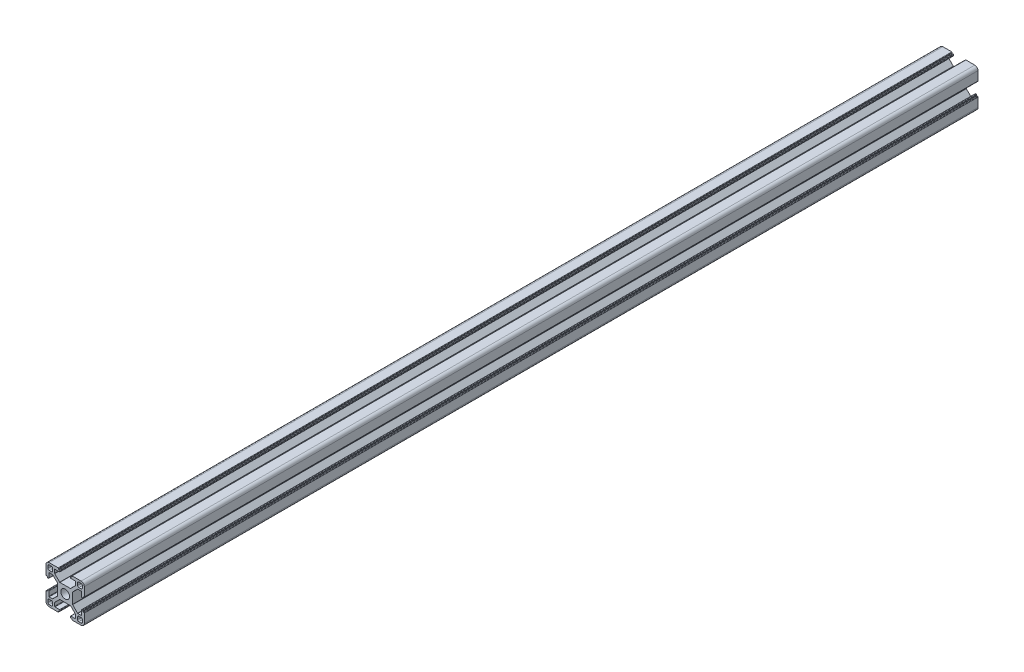
SolidWorks part; units mm, degrees
ref_plane "Front Plane" through (0, 0, 0) normal (0, 0, 1) x (1, 0, 0)
ref_plane "Top Plane" through (0, 0, 0) normal (0, 1, 0) x (1, 0, 0)
ref_plane "Right Plane" through (0, 0, 0) normal (1, 0, 0) x (0, 0, -1)
sketch "Model" plane through (0, 0, 0) normal (0, 0, 1) x (1, 0, 0)
  line L0 (21.5, 27) -> (25, 27)
  line L1 (27, 25) -> (27, 21.5)
  line L2 (25, 19.5) -> (21.5, 19.5)
  line L3 (19.5, 21.5) -> (19.5, 25)
  line L4 (21.5, -27) -> (25, -27)
  line L5 (27, -25) -> (27, -21.5)
  line L6 (25, -19.5) -> (21.5, -19.5)
  line L7 (19.5, -21.5) -> (19.5, -25)
  line L8 (0, 11.6) -> (-8.2402, 11.6)
  line L9 (-8.6645, 11.7757) -> (-16.3243, 19.4355)
  line L10 (-16.5, 19.8598) -> (-16.5, 25)
  line L11 (-15.9, 25.6) -> (-8.8, 25.6)
  line L12 (-8.2, 26.2) -> (-8.2, 27.4)
  line L13 (-8.8, 28) -> (-9.8, 28)
  line L14 (-10.4, 28.6) -> (-10.4, 29.4)
  line L15 (-11, 30) -> (-25, 30)
  line L16 (-30, 25) -> (-30, 11)
  line L17 (-29.4, 10.4) -> (-28.6, 10.4)
  line L18 (-28, 9.8) -> (-28, 8.8)
  line L19 (-27.4, 8.2) -> (-26.2, 8.2)
  line L20 (-25.6, 8.8) -> (-25.6, 15.9)
  line L21 (-25, 16.5) -> (-19.8598, 16.5)
  line L22 (-19.4355, 16.3243) -> (-11.7757, 8.6645)
  line L23 (-11.6, 8.2402) -> (-11.6, 0)
  line L24 (-11.6, 0) -> (-11.6, -8.2402)
  line L25 (-11.7757, -8.6645) -> (-19.4355, -16.3243)
  line L26 (-19.8598, -16.5) -> (-25, -16.5)
  line L27 (-25.6, -15.9) -> (-25.6, -8.8)
  line L28 (-26.2, -8.2) -> (-27.4, -8.2)
  line L29 (-28, -8.8) -> (-28, -9.8)
  line L30 (-28.6, -10.4) -> (-29.4, -10.4)
  line L31 (-30, -11) -> (-30, -25)
  line L32 (-25, -30) -> (-11, -30)
  line L33 (-10.4, -29.4) -> (-10.4, -28.6)
  line L34 (-9.8, -28) -> (-8.8, -28)
  line L35 (-8.2, -27.4) -> (-8.2, -26.2)
  line L36 (-8.8, -25.6) -> (-15.9, -25.6)
  line L37 (-16.5, -25) -> (-16.5, -19.8598)
  line L38 (-16.3243, -19.4355) -> (-8.6645, -11.7757)
  line L39 (-8.2402, -11.6) -> (0, -11.6)
  line L40 (0, -11.6) -> (8.2402, -11.6)
  line L41 (8.6645, -11.7757) -> (16.3243, -19.4355)
  line L42 (16.5, -19.8598) -> (16.5, -25)
  line L43 (15.9, -25.6) -> (8.8, -25.6)
  line L44 (8.2, -26.2) -> (8.2, -27.4)
  line L45 (8.8, -28) -> (9.8, -28)
  line L46 (10.4, -28.6) -> (10.4, -29.4)
  line L47 (11, -30) -> (25, -30)
  line L48 (30, -25) -> (30, -11)
  line L49 (29.4, -10.4) -> (28.6, -10.4)
  line L50 (28, -9.8) -> (28, -8.8)
  line L51 (27.4, -8.2) -> (26.2, -8.2)
  line L52 (25.6, -8.8) -> (25.6, -15.9)
  line L53 (25, -16.5) -> (19.8598, -16.5)
  line L54 (19.4355, -16.3243) -> (11.7757, -8.6645)
  line L55 (11.6, -8.2402) -> (11.6, 0)
  line L56 (11.6, 0) -> (11.6, 8.2402)
  line L57 (11.7757, 8.6645) -> (19.6113, 16.5)
  line L58 (19.6113, 16.5) -> (25, 16.5)
  line L59 (25.6, 15.9) -> (25.6, 8.8)
  line L60 (26.2, 8.2) -> (27.4, 8.2)
  line L61 (28, 8.8) -> (28, 9.8)
  line L62 (28.6, 10.4) -> (29.4, 10.4)
  line L63 (30, 11) -> (30, 25)
  line L64 (25, 30) -> (11, 30)
  line L65 (10.4, 29.4) -> (10.4, 28.6)
  line L66 (9.8, 28) -> (8.8, 28)
  line L67 (8.2, 27.4) -> (8.2, 26.2)
  line L68 (8.8, 25.6) -> (15.9, 25.6)
  line L69 (16.5, 25) -> (16.5, 19.8598)
  line L70 (16.3243, 19.4355) -> (8.6645, 11.7757)
  line L71 (8.2402, 11.6) -> (0, 11.6)
  line L72 (-21.5, -27) -> (-25, -27)
  line L73 (-27, -25) -> (-27, -21.5)
  line L74 (-25, -19.5) -> (-21.5, -19.5)
  line L75 (-19.5, -21.5) -> (-19.5, -25)
  line L76 (-21.5, 27) -> (-25, 27)
  line L77 (-27, 25) -> (-27, 21.5)
  line L78 (-25, 19.5) -> (-21.5, 19.5)
  line L79 (-19.5, 21.5) -> (-19.5, 25)
  circle A0 centre (0, 0) radius 6.8
  arc A1 (21.5, 27) -> (19.5, 25) centre (21.5, 25) ccw
  arc A2 (27, 25) -> (25, 27) centre (25, 25) ccw
  arc A3 (25, 19.5) -> (27, 21.5) centre (25, 21.5) ccw
  arc A4 (19.5, 21.5) -> (21.5, 19.5) centre (21.5, 21.5) ccw
  arc A5 (19.5, -25) -> (21.5, -27) centre (21.5, -25) ccw
  arc A6 (25, -27) -> (27, -25) centre (25, -25) ccw
  arc A7 (27, -21.5) -> (25, -19.5) centre (25, -21.5) ccw
  arc A8 (21.5, -19.5) -> (19.5, -21.5) centre (21.5, -21.5) ccw
  arc A9 (-8.6645, 11.7757) -> (-8.2402, 11.6) centre (-8.2402, 12.2) ccw
  arc A10 (-16.5, 19.8598) -> (-16.3243, 19.4355) centre (-15.9, 19.8598) ccw
  arc A11 (-15.9, 25.6) -> (-16.5, 25) centre (-15.9, 25) ccw
  arc A12 (-8.8, 25.6) -> (-8.2, 26.2) centre (-8.8, 26.2) ccw
  arc A13 (-8.2, 27.4) -> (-8.8, 28) centre (-8.8, 27.4) ccw
  arc A14 (-10.4, 28.6) -> (-9.8, 28) centre (-9.8, 28.6) ccw
  arc A15 (-10.4, 29.4) -> (-11, 30) centre (-11, 29.4) ccw
  arc A16 (-25, 30) -> (-30, 25) centre (-25, 25) ccw
  arc A17 (-30, 11) -> (-29.4, 10.4) centre (-29.4, 11) ccw
  arc A18 (-28, 9.8) -> (-28.6, 10.4) centre (-28.6, 9.8) ccw
  arc A19 (-28, 8.8) -> (-27.4, 8.2) centre (-27.4, 8.8) ccw
  arc A20 (-26.2, 8.2) -> (-25.6, 8.8) centre (-26.2, 8.8) ccw
  arc A21 (-25, 16.5) -> (-25.6, 15.9) centre (-25, 15.9) ccw
  arc A22 (-19.4355, 16.3243) -> (-19.8598, 16.5) centre (-19.8598, 15.9) ccw
  arc A23 (-11.6, 8.2402) -> (-11.7757, 8.6645) centre (-12.2, 8.2402) ccw
  arc A24 (-11.7757, -8.6645) -> (-11.6, -8.2402) centre (-12.2, -8.2402) ccw
  arc A25 (-19.8598, -16.5) -> (-19.4355, -16.3243) centre (-19.8598, -15.9) ccw
  arc A26 (-25.6, -15.9) -> (-25, -16.5) centre (-25, -15.9) ccw
  arc A27 (-25.6, -8.8) -> (-26.2, -8.2) centre (-26.2, -8.8) ccw
  arc A28 (-27.4, -8.2) -> (-28, -8.8) centre (-27.4, -8.8) ccw
  arc A29 (-28.6, -10.4) -> (-28, -9.8) centre (-28.6, -9.8) ccw
  arc A30 (-29.4, -10.4) -> (-30, -11) centre (-29.4, -11) ccw
  arc A31 (-30, -25) -> (-25, -30) centre (-25, -25) ccw
  arc A32 (-11, -30) -> (-10.4, -29.4) centre (-11, -29.4) ccw
  arc A33 (-9.8, -28) -> (-10.4, -28.6) centre (-9.8, -28.6) ccw
  arc A34 (-8.8, -28) -> (-8.2, -27.4) centre (-8.8, -27.4) ccw
  arc A35 (-8.2, -26.2) -> (-8.8, -25.6) centre (-8.8, -26.2) ccw
  arc A36 (-16.5, -25) -> (-15.9, -25.6) centre (-15.9, -25) ccw
  arc A37 (-16.3243, -19.4355) -> (-16.5, -19.8598) centre (-15.9, -19.8598) ccw
  arc A38 (-8.2402, -11.6) -> (-8.6645, -11.7757) centre (-8.2402, -12.2) ccw
  arc A39 (8.6645, -11.7757) -> (8.2402, -11.6) centre (8.2402, -12.2) ccw
  arc A40 (16.5, -19.8598) -> (16.3243, -19.4355) centre (15.9, -19.8598) ccw
  arc A41 (15.9, -25.6) -> (16.5, -25) centre (15.9, -25) ccw
  arc A42 (8.8, -25.6) -> (8.2, -26.2) centre (8.8, -26.2) ccw
  arc A43 (8.2, -27.4) -> (8.8, -28) centre (8.8, -27.4) ccw
  arc A44 (10.4, -28.6) -> (9.8, -28) centre (9.8, -28.6) ccw
  arc A45 (10.4, -29.4) -> (11, -30) centre (11, -29.4) ccw
  arc A46 (25, -30) -> (30, -25) centre (25, -25) ccw
  arc A47 (30, -11) -> (29.4, -10.4) centre (29.4, -11) ccw
  arc A48 (28, -9.8) -> (28.6, -10.4) centre (28.6, -9.8) ccw
  arc A49 (28, -8.8) -> (27.4, -8.2) centre (27.4, -8.8) ccw
  arc A50 (26.2, -8.2) -> (25.6, -8.8) centre (26.2, -8.8) ccw
  arc A51 (25, -16.5) -> (25.6, -15.9) centre (25, -15.9) ccw
  arc A52 (19.4355, -16.3243) -> (19.8598, -16.5) centre (19.8598, -15.9) ccw
  arc A53 (11.6, -8.2402) -> (11.7757, -8.6645) centre (12.2, -8.2402) ccw
  arc A54 (11.7757, 8.6645) -> (11.6, 8.2402) centre (12.2, 8.2402) ccw
  arc A55 (25.6, 15.9) -> (25, 16.5) centre (25, 15.9) ccw
  arc A56 (25.6, 8.8) -> (26.2, 8.2) centre (26.2, 8.8) ccw
  arc A57 (27.4, 8.2) -> (28, 8.8) centre (27.4, 8.8) ccw
  arc A58 (28.6, 10.4) -> (28, 9.8) centre (28.6, 9.8) ccw
  arc A59 (29.4, 10.4) -> (30, 11) centre (29.4, 11) ccw
  arc A60 (30, 25) -> (25, 30) centre (25, 25) ccw
  arc A61 (11, 30) -> (10.4, 29.4) centre (11, 29.4) ccw
  arc A62 (9.8, 28) -> (10.4, 28.6) centre (9.8, 28.6) ccw
  arc A63 (8.8, 28) -> (8.2, 27.4) centre (8.8, 27.4) ccw
  arc A64 (8.2, 26.2) -> (8.8, 25.6) centre (8.8, 26.2) ccw
  arc A65 (16.5, 25) -> (15.9, 25.6) centre (15.9, 25) ccw
  arc A66 (16.3243, 19.4355) -> (16.5, 19.8598) centre (15.9, 19.8598) ccw
  arc A67 (8.2402, 11.6) -> (8.6645, 11.7757) centre (8.2402, 12.2) ccw
  arc A68 (-21.5, -27) -> (-19.5, -25) centre (-21.5, -25) ccw
  arc A69 (-27, -25) -> (-25, -27) centre (-25, -25) ccw
  arc A70 (-25, -19.5) -> (-27, -21.5) centre (-25, -21.5) ccw
  arc A71 (-19.5, -21.5) -> (-21.5, -19.5) centre (-21.5, -21.5) ccw
  arc A72 (-19.5, 25) -> (-21.5, 27) centre (-21.5, 25) ccw
  arc A73 (-25, 27) -> (-27, 25) centre (-25, 25) ccw
  arc A74 (-27, 21.5) -> (-25, 19.5) centre (-25, 21.5) ccw
  arc A75 (-21.5, 19.5) -> (-19.5, 21.5) centre (-21.5, 21.5) ccw
extrude "Boss-Extrude1" add sketch "Model" along normal blind 1400
scale "Scale1" bodies to scale 101 scale about centroid uniform scaling yes scale factor 0.5
